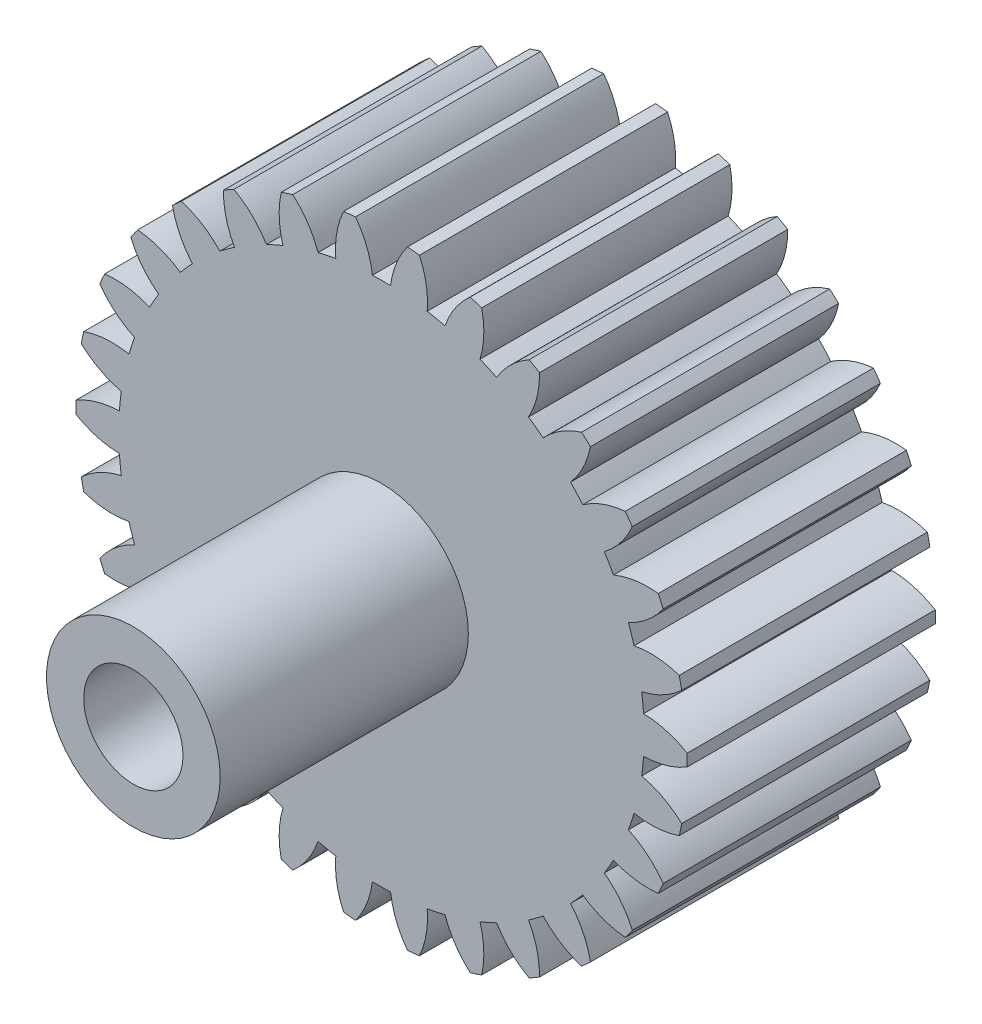
SolidWorks part; units mm, degrees
ref_plane "Front" through (0, 0, 0) normal (0, 0, 1) x (1, 0, 0)
ref_plane "Top" through (0, 0, 0) normal (0, 1, 0) x (1, 0, 0)
ref_plane "Right" through (0, 0, 0) normal (1, 0, 0) x (0, 0, -1)
sketch "Эскиз1" plane through (0, 0, 0) normal (0, 0, 1) x (1, 0, 0)
  circle A0 centre (0, 0) radius 10.5875 construction
  circle A1 centre (0, 0) radius 11.5 construction
  circle A2 centre (0, 0) radius 12.32
  circle A3 centre (0, 0) radius 10.805 construction
  dimension "D1" = 21.175
  dimension "D2" = 23
  dimension "D3" = 24.64
  dimension "D4" = 21.61
extrude "Бобышка-Вытянуть1" add sketch "Эскиз1" along normal mid plane 10
sketch "Эскиз2" plane through (0, 0, 5) normal (0, 0, 1) x (1, 0, 0)
  line L0 (-0.9448, 15.1928) -> (0, 0) construction
  line L1 (-0.7321, 11.7723) -> (-4.9391, 9.6101) construction
  line L2 (-0.6, 11.4843) -> (0.6, 11.4843) construction
  line L3 (0, 0) -> (0, 12.32) construction
  circle A0 centre (0, 0) radius 12.32 construction
  circle A1 centre (0, 0) radius 10.805 construction
  arc A2 (-1.4587, 12.7367) -> (-0.3658, 10.5812) centre (-3.8896, 10.1495) cw
  circle A3 centre (0, 0) radius 10.5875 construction
  circle A4 centre (0, 0) radius 11.5 construction
  arc A5 (1.4587, 12.7367) -> (0.3658, 10.5812) centre (3.8896, 10.1495) ccw
  arc A6 (-0.3658, 10.5812) -> (0.3658, 10.5812) centre (0, 0) cw
  circle A8 centre (0, 0) radius 12.82
  arc A9 (1.4587, 12.7367) -> (-1.4587, 12.7367) centre (0, 0) ccw
  point P3 (-0.7321, 11.7723)
  dimension "D1" = 0.525
  dimension "D2" = 1.2
  dimension "D3" = 4.7301
  dimension "D4" = 1.18
  dimension "D5" = 0.5
sketch "Эскиз4" plane through (0, 0, 0) normal (0, 1, 0) x (1, 0, 0)
  line L0 (0, 5) -> (0, -5)
  line L1 (12.32, 5) -> (-12.32, 5) construction
  line L3 (-12.32, -5) -> (12.32, -5) construction
  line L4 (0, -50) -> (0, 50) construction
  dimension "D1" = 0
curve "Кривая1"
sketch "Эскиз5" plane through (0, 0, -5) normal (0, 0, 1) x (1, 0, 0)
  line L0 (-0.9448, 15.1928) -> (0, 0) construction
  line L1 (-0.7321, 11.7723) -> (-4.9391, 9.6101) construction
  line L2 (-0.6, 11.4843) -> (0.6, 11.4843) construction
  line L3 (0, 0) -> (0, 12.32) construction
  arc A2 (-1.4587, 12.7367) -> (-0.3658, 10.5812) centre (-3.8896, 10.1495) cw
  arc A5 (1.4587, 12.7367) -> (0.3658, 10.5812) centre (3.8896, 10.1495) ccw
  arc A6 (-0.3658, 10.5812) -> (0.3658, 10.5812) centre (0, 0) cw
  arc A9 (1.4587, 12.7367) -> (-1.4587, 12.7367) centre (0, 0) ccw
  point P3 (-0.7321, 11.7723)
loft "Вырез-По сечениям1" cut profiles "Эскиз5", "Эскиз2"
pattern_circular "Круговой массив1" count 30 over 360 about axis through (0, 0, 0) along (0, 0, 1) of "Вырез-По сечениям1"
sketch "Эскиз6" plane through (0, 0, 5) normal (0, 0, 1) x (1, 0, 0)
  circle A0 centre (0, 0) radius 3.5
  dimension "D1" = 7
extrude "Бобышка-Вытянуть2" add sketch "Эскиз6" along normal blind 10
sketch "Эскиз7" plane through (0, 0, 15) normal (0, 0, 1) x (1, 0, 0)
  circle A0 centre (0, 0) radius 2
  dimension "D1" = 4
extrude "Вырез-Вытянуть1" cut sketch "Эскиз7" against normal blind 3
sketch "Эскиз8" plane through (0, 0, 12) normal (0, 0, 1) x (1, 0, 0)
  line L0 (-1.2639, 1.55) -> (1.2639, 1.55)
  circle A0 centre (0, 0) radius 2 construction
  circle M2 centre (0, 0) radius 2
  dimension "D1" = 1.55
extrude "Вырез-Вытянуть2" cut sketch "Эскиз8" against normal blind 7 and the other way through all contours L0 M2
